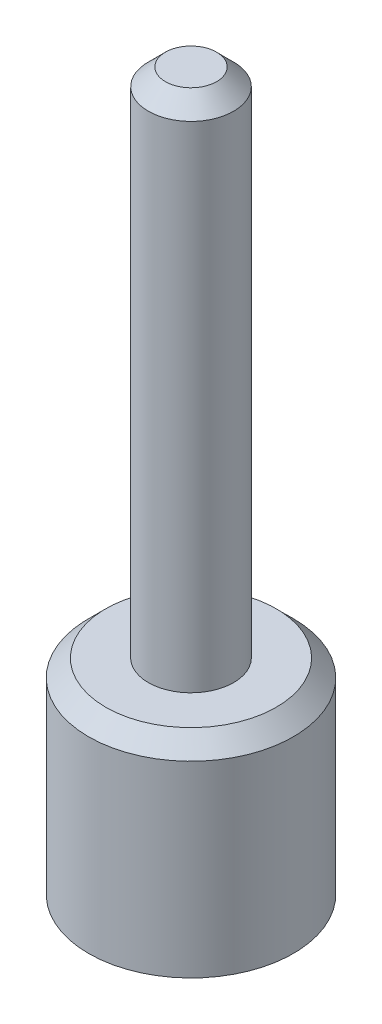
SolidWorks part; units mm, degrees
ref_plane "Front" through (0, 0, 0) normal (0, 0, 1) x (1, 0, 0)
ref_plane "Top" through (0, 0, 0) normal (0, 1, 0) x (1, 0, 0)
ref_plane "Right" through (0, 0, 0) normal (1, 0, 0) x (0, 0, -1)
sketch "Эскиз1" plane through (0, 0, 0) normal (0, 1, 0) x (1, 0, 0)
  circle A0 centre (0, 0) radius 6
  dimension "D1" = 12
extrude "Вытянуть1" add sketch "Эскиз1" along normal blind 12
sketch "Эскиз2" plane through (0, 12, 0) normal (0, 1, 0) x (1, 0, 0)
  circle A0 centre (0, 0) radius 2.5
  dimension "D1" = 5
extrude "Вытянуть2" add sketch "Эскиз2" along normal blind 30
chamfer "Фаска1" distance 1 angle 45 2 edges at (0, 12, 6) (0, 42, 2.5)
